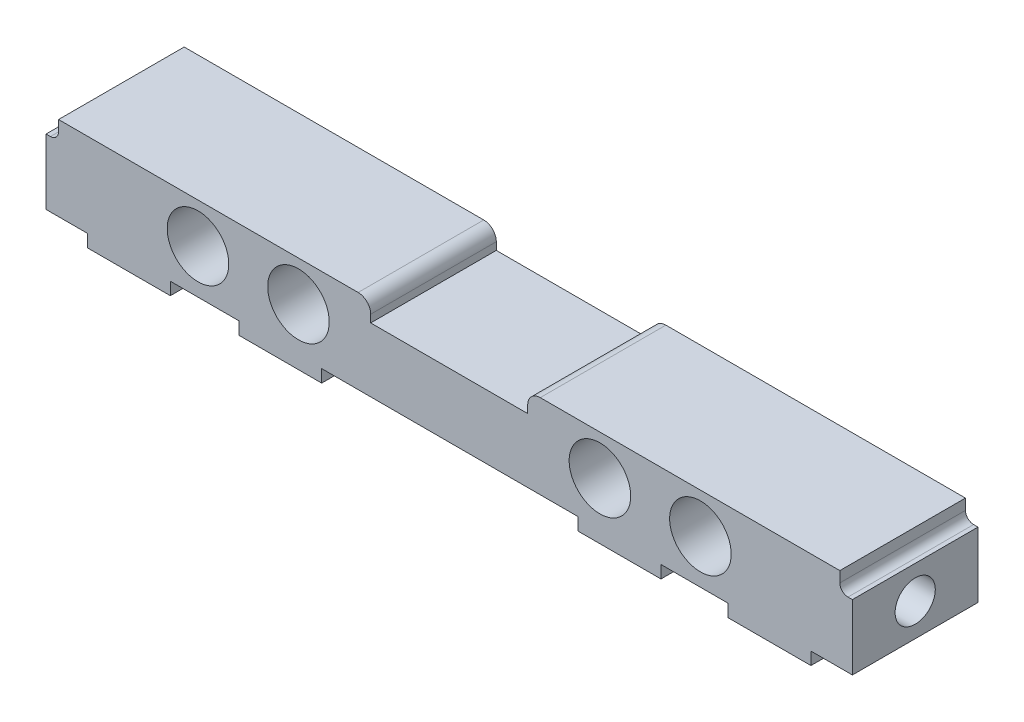
SolidWorks part; units mm, degrees
ref_plane "Front Plane" through (0, 0, 0) normal (0, 0, 1) x (1, 0, 0)
ref_plane "Top Plane" through (0, 0, 0) normal (0, 1, 0) x (1, 0, 0)
ref_plane "Right Plane" through (0, 0, 0) normal (1, 0, 0) x (0, 0, -1)
sketch "Sketch2" plane through (0, 0, 0) normal (0, 0, 1) x (1, 0, 0)
  line L0 (-7.7382, 3.19) -> (7.8618, 3.19)
  line L1 (-7.7382, 3.34) -> (7.8618, 3.34)
  line L2 (31.1, 3.19) -> (7.8618, 3.19)
  line L3 (31.1, 2.34) -> (31.1, 3.19)
  line L4 (32.1, 1.69) -> (31.75, 1.69)
  line L5 (32.1, -3.51) -> (32.1, 1.69)
  line L6 (28.8, -3.51) -> (32.1, -3.51)
  line L7 (28.8, -4.51) -> (28.8, -3.51)
  line L8 (22.2, -4.51) -> (28.8, -4.51)
  line L9 (22.2, -3.51) -> (22.2, -4.51)
  line L10 (16.86, -3.51) -> (22.2, -3.51)
  line L11 (16.86, -4.51) -> (16.86, -3.51)
  line L12 (10.26, -4.51) -> (16.86, -4.51)
  line L13 (10.26, -3.51) -> (10.26, -4.51)
  line L14 (-10.15, -3.51) -> (10.26, -3.51)
  line L15 (-10.15, -4.51) -> (-10.15, -3.51)
  line L16 (-16.75, -4.51) -> (-10.15, -4.51)
  line L17 (-16.75, -3.51) -> (-16.75, -4.51)
  line L18 (-22.2, -3.51) -> (-16.75, -3.51)
  line L19 (-22.2, -4.51) -> (-22.2, -3.51)
  line L20 (-28.8, -4.51) -> (-22.2, -4.51)
  line L21 (-28.8, -3.51) -> (-28.8, -4.51)
  line L22 (-32.1, -3.51) -> (-28.8, -3.51)
  line L23 (-32.1, 1.69) -> (-32.1, -3.51)
  line L24 (-31.75, 1.69) -> (-32.1, 1.69)
  line L25 (-31.1, 3.19) -> (-31.1, 2.34)
  line L26 (-7.7382, 3.19) -> (-31.1, 3.19)
  line L57 (-31.75, 1.84) -> (-32.25, 1.84)
  line L58 (-31.25, 3.34) -> (-31.25, 2.34)
  line L59 (-7.7382, 3.34) -> (-31.25, 3.34)
  line L63 (31.25, 3.34) -> (7.8618, 3.34)
  line L64 (31.25, 2.34) -> (31.25, 3.34)
  line L65 (32.25, 1.84) -> (31.75, 1.84)
  line L66 (32.25, -3.66) -> (32.25, 1.84)
  line L67 (28.95, -3.66) -> (32.25, -3.66)
  line L68 (28.95, -4.66) -> (28.95, -3.66)
  line L69 (22.05, -4.66) -> (28.95, -4.66)
  line L70 (22.05, -3.66) -> (22.05, -4.66)
  line L71 (17.01, -3.66) -> (22.05, -3.66)
  line L72 (17.01, -4.66) -> (17.01, -3.66)
  line L73 (10.11, -4.66) -> (17.01, -4.66)
  line L74 (10.11, -3.66) -> (10.11, -4.66)
  line L75 (-10, -3.66) -> (10.11, -3.66)
  line L76 (-10, -4.66) -> (-10, -3.66)
  line L77 (-16.9, -4.66) -> (-10, -4.66)
  line L78 (-16.9, -3.66) -> (-16.9, -4.66)
  line L79 (-22.05, -3.66) -> (-16.9, -3.66)
  line L80 (-22.05, -4.66) -> (-22.05, -3.66)
  line L81 (-28.95, -4.66) -> (-22.05, -4.66)
  line L82 (-28.95, -3.66) -> (-28.95, -4.66)
  line L83 (-32.25, -3.66) -> (-28.95, -3.66)
  line L84 (-32.25, 1.84) -> (-32.25, -3.66)
  arc A0 (31.1, 2.34) -> (31.75, 1.69) centre (31.75, 2.34) ccw
  arc A1 (-31.75, 1.69) -> (-31.1, 2.34) centre (-31.75, 2.34) ccw
  arc A12 (-31.75, 1.84) -> (-31.25, 2.34) centre (-31.75, 2.34) ccw
  arc A17 (31.25, 2.34) -> (31.75, 1.84) centre (31.75, 2.34) ccw
  dimension "D1" = 0.15
extrude "Boss-Extrude1" add sketch "Sketch2" along normal blind 10 contours A1 L23 L22 L21 L20 L19 L18 L17 L16 L15 L14 L13 L12 L11 L10 L9 L8 L7 L6 L5 A0 L3 L2 L0 L26 L25
sketch "Sketch3" plane through (0, 0, 10) normal (0, 0, 1) x (1, 0, 0)
  line L0 (-12, 0) -> (12, 0)
  line L1 (-20, 0) -> (20, 0)
  circle A0 centre (-20, 0) radius 2.45
  circle A1 centre (-12, 0) radius 2.45
  circle A2 centre (12, 0) radius 2.45
  circle A3 centre (20, 0) radius 2.45
  point P4 (0, 0)
  point P8 (0, 0)
  dimension "D3" = 4.9
  dimension "D4" = 4.9
  dimension "D5" = 4.9
  dimension "D6" = 4.9
  dimension "D1" = 24
  dimension "D2" = 40
extrude "Cut-Extrude1" cut sketch "Sketch3" against normal blind 11 contours A0 | A1 | A2 | A3
sketch "Sketch4" plane through (32.1, 0, 0) normal (1, 0, 0) x (0, 0, -1)
  line L0 (0, -0.91) -> (-10, -0.91)
  line L1 (0, -3.51) -> (0, 1.69) construction
  line L2 (-10, -3.51) -> (-10, 1.69) construction
  circle A0 centre (-5, -0.91) radius 1.6
  dimension "D1" = 3.2
extrude "Cut-Extrude2" cut sketch "Sketch4" against normal blind 5 contours A0
sketch "Sketch5" plane through (-32.1, 0, 0) normal (-1, 0, 0) x (0, 0, 1)
  line L0 (10, -0.91) -> (0, -0.91)
  line L1 (10, 1.69) -> (10, -3.51) construction
  line L2 (0, 1.69) -> (0, -3.51) construction
  circle A0 centre (5, -0.91) radius 1.6
  dimension "D1" = 3.2
extrude "Cut-Extrude3" cut sketch "Sketch5" against normal blind 5 contours A0
sketch "Sketch6" plane through (0, 0, 10) normal (0, 0, 1) x (1, 0, 0)
  line L0 (0, 3.19) -> (0, 2.39)
  line L1 (31.1, 3.19) -> (-31.1, 3.19) construction
  line L3 (-6.25, 3.19) -> (6.25, 3.19)
  line L4 (-6.25, 3.19) -> (-6.25, 1.59)
  line L5 (-6.25, 1.59) -> (6.25, 1.59)
  line L6 (6.25, 3.19) -> (6.25, 1.59)
  line L7 (-6.25, 3.19) -> (6.25, 1.59) construction
  line L8 (-6.25, 1.59) -> (6.25, 3.19) construction
  dimension "D1" = 0.8
  dimension "D2" = 1.6
  dimension "D3" = 12.5
extrude "Cut-Extrude4" cut sketch "Sketch6" against normal blind 11
fillet "Fillet1" radius 1 2 edges at (6.25, 3.19, 5) (-6.25, 3.19, 5)
